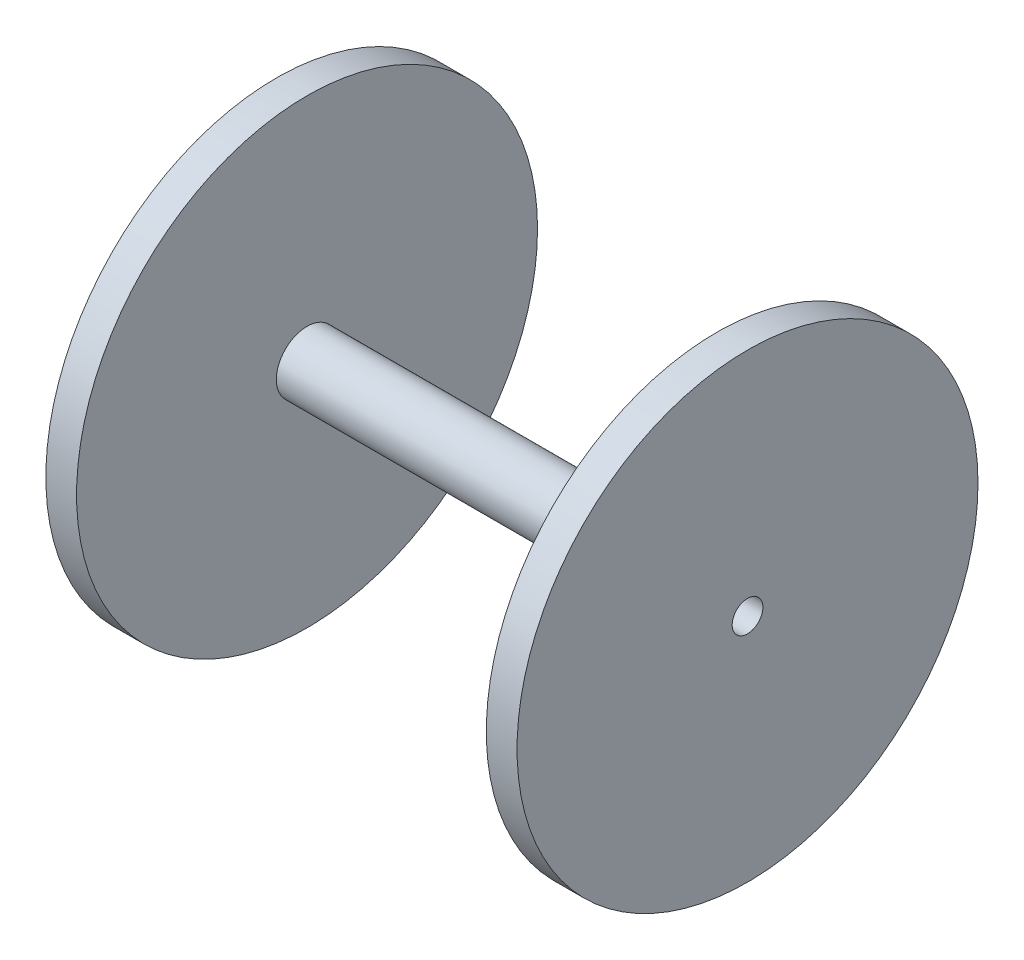
SolidWorks part; units mm, degrees
ref_plane "Front Plane" through (0, 0, 0) normal (0, 0, 1) x (1, 0, 0)
ref_plane "Top Plane" through (0, 0, 0) normal (0, 1, 0) x (1, 0, 0)
ref_plane "Right Plane" through (0, 0, 0) normal (1, 0, 0) x (0, 0, -1)
sketch "Sketch1" plane through (0, 0, 0) normal (1, 0, 0) x (0, 0, -1)
  circle A0 centre (0, 0) radius 3
  circle A1 centre (0, 0) radius 1.5
extrude "Boss-Extrude1" add sketch "Sketch1" along normal blind 40
ref_plane "Plane1" through (20, 0, 0) normal (1, 0, 0) x (0, 0, -1)
sketch "Sketch2" plane through (40, 0, 0) normal (1, 0, 0) x (0, 0, -1)
  circle A0 centre (0, 0) radius 22.5
  circle A1 centre (0, 0) radius 1.5
extrude "Boss-Extrude2" add sketch "Sketch2" along normal blind 3
mirror "Mirror1" about plane through (20, 0, 0) normal (1, 0, 0) of "Boss-Extrude2"
sketch "Sketch3" plane through (43, 0, 0) normal (1, 0, 0) x (0, 0, -1)
  line L0 (0, 0) -> (1, 0) construction
  line L1 (1, 1.118) -> (1, -1.118)
  arc A0 (1, -1.118) -> (1, 1.118) centre (0, 0) ccw
  point P7 (1, 0)
sketch "Sketch4" plane through (-3, 0, 0) normal (-1, 0, 0) x (0, 0, 1)
  line L0 (-1, 1.118) -> (-1, -1.118)
  arc A0 (-1, 1.118) -> (-1, -1.118) centre (0, 0) ccw
extrude "Boss-Extrude4" add sketch "Sketch4" against normal blind 10
